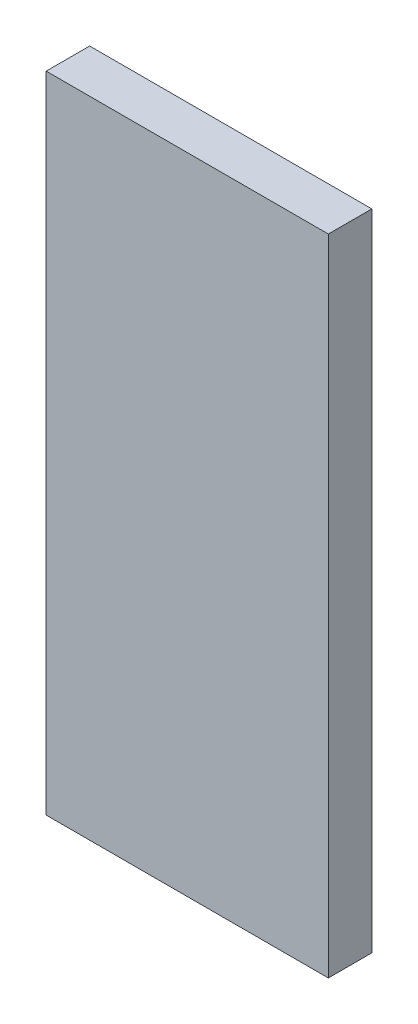
SolidWorks part; units mm, degrees
ref_plane "Front Plane" through (0, 0, 0) normal (0, 0, 1) x (1, 0, 0)
ref_plane "Top Plane" through (0, 0, 0) normal (0, 1, 0) x (1, 0, 0)
ref_plane "Right Plane" through (0, 0, 0) normal (1, 0, 0) x (0, 0, -1)
ref_plane "Plane4" through (0, 0, 9.25) normal (0, 0, 1) x (1, 0, 0)
sketch "Sketch1" plane through (0, 0, 9.25) normal (0, 0, 1) x (1, 0, 0)
  line L0 (-30, 68.5) -> (-30, -68.5)
  line L1 (-30, -68.5) -> (30, -68.5)
  line L2 (30, -68.5) -> (30, 68.5)
  line L3 (30, 68.5) -> (-30, 68.5)
  dimension "D1" = 30
  dimension "D2" = 30
  dimension "D3" = 68.5
  dimension "D4" = 68.5
extrude "Boss-Extrude1" add sketch "Sketch1" against normal blind 9.25
